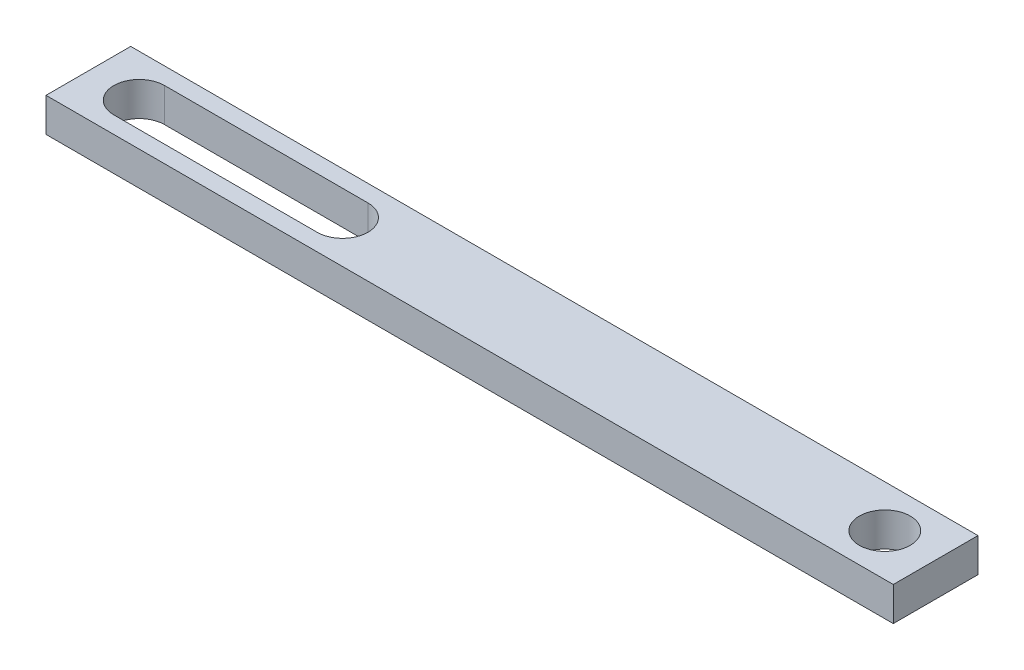
SolidWorks part; units mm, degrees
ref_plane "Front Plane" through (0, 0, 0) normal (0, 0, 1) x (1, 0, 0)
ref_plane "Top Plane" through (0, 0, 0) normal (0, 1, 0) x (1, 0, 0)
ref_plane "Right Plane" through (0, 0, 0) normal (1, 0, 0) x (0, 0, -1)
sketch "Sketch2" plane through (0, 0, 0) normal (0, 1, 0) x (1, 0, 0)
  line L0 (3, 4) -> (15, 4)
  line L1 (0, 0) -> (50, 0)
  line L2 (0, 0) -> (0, 5)
  line L3 (0, 5) -> (50, 5)
  line L4 (50, 0) -> (50, 5)
  line L5 (15, 1) -> (3, 1)
  arc A0 (3, 4) -> (3, 1) centre (3, 2.5) ccw
  arc A1 (15, 1) -> (15, 4) centre (15, 2.5) ccw
  circle A2 centre (47, 2.5) radius 1.5
  dimension "D1" = 3
  dimension "D4" = 3
  dimension "D7" = 3
  dimension "D2" = 50
  dimension "D3" = 5
  dimension "D5" = 2.5
  dimension "D6" = 15
  dimension "D8" = 3
  dimension "D9" = 2.5
extrude "Boss-Extrude1" add sketch "Sketch2" along normal blind 2
sketch "Sketch3" plane through (0, 2, 0) normal (0, 1, 0) x (1, 0, 0)
  line L0 (3, 2.5) -> (15, 2.5)
  line L1 (3, 1) -> (15, 1) construction
  line L2 (15, 4) -> (3, 4) construction
  line L3 (3, 1) -> (15, 1)
  line L4 (15, 4) -> (3, 4)
  circle A0 centre (47, 2.5) radius 1.5
  arc A1 (3, 4) -> (3, 1) centre (3, 2.5) ccw construction
  arc A2 (15, 1) -> (15, 4) centre (15, 2.5) ccw construction
  arc A3 (15, 1) -> (15, 4) centre (15, 2.5) ccw
  arc A4 (3, 4) -> (3, 1) centre (3, 2.5) ccw
  dimension "D1" = 3
